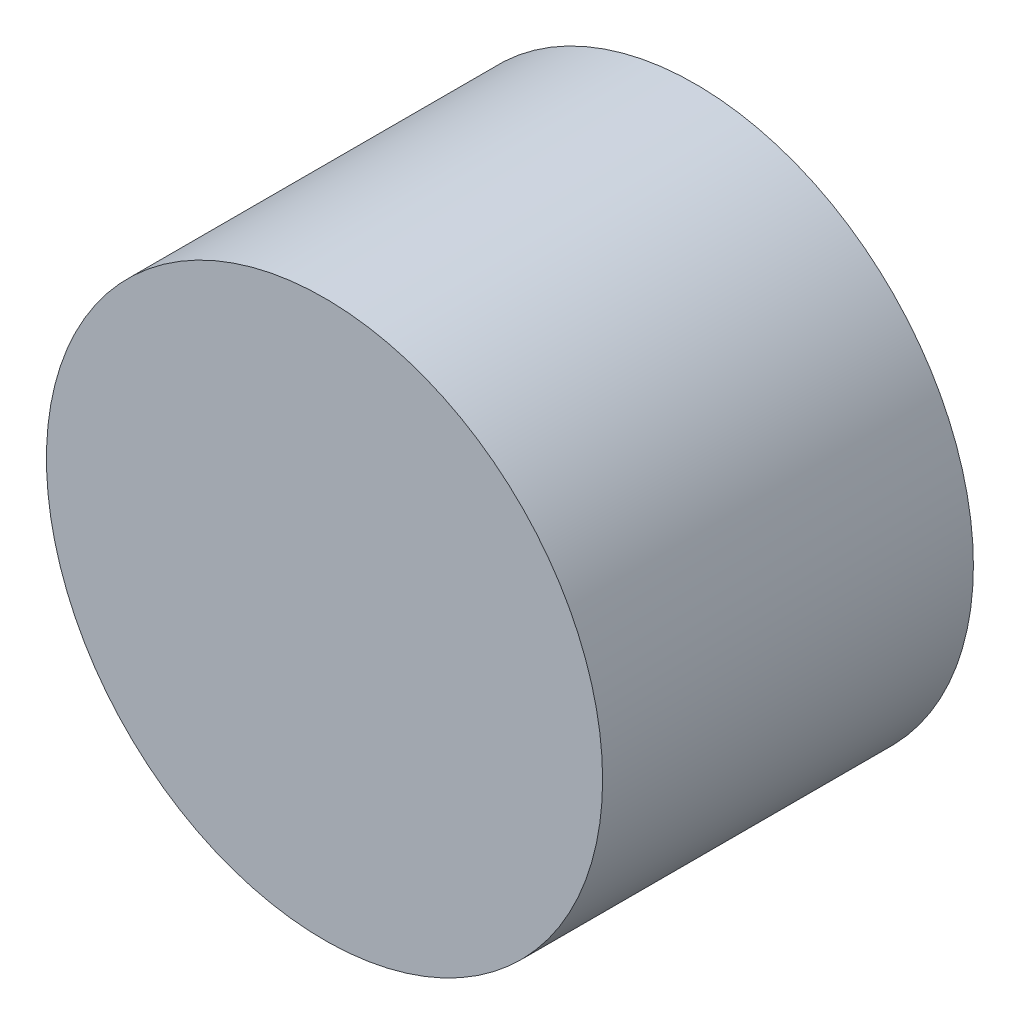
SolidWorks part; units mm, degrees
ref_plane "Front Plane" through (0, 0, 0) normal (0, 0, 1) x (1, 0, 0)
ref_plane "Top Plane" through (0, 0, 0) normal (0, 1, 0) x (1, 0, 0)
ref_plane "Right Plane" through (0, 0, 0) normal (1, 0, 0) x (0, 0, -1)
sketch "Sketch2" plane through (0, 0, 0) normal (0, 0, 1) x (1, 0, 0)
  circle A0 centre (0, 0) radius 7.5
  dimension "D1" = 15
extrude "Boss-Extrude1" add sketch "Sketch2" along normal blind 10
sketch "Sketch3" plane through (0, 0, 0) normal (0, 0, -1) x (-1, 0, 0)
  circle A0 centre (0, 0) radius 3
extrude "Cut-Extrude1" cut sketch "Sketch3" against normal offset from surface (9.8 mm away) 0.2 up to face at (7.5, 0, 10)
